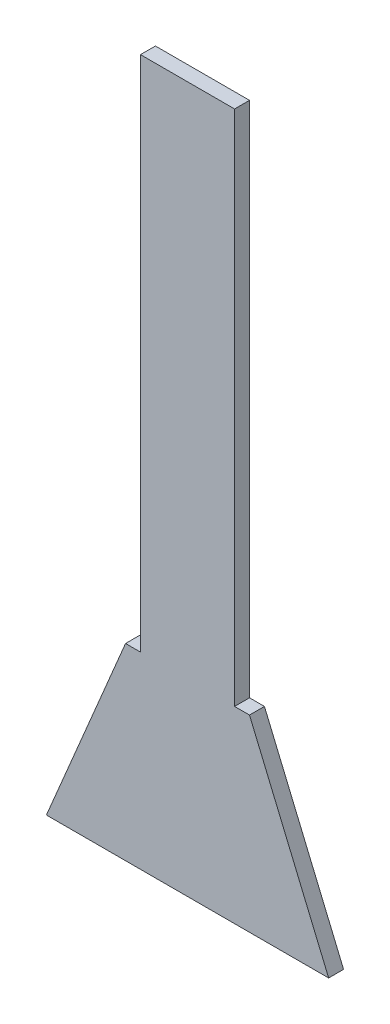
SolidWorks part; units mm, degrees
material "ABS"
ref_plane "Plan de face" through (0, 0, 0) normal (0, 0, 1) x (1, 0, 0)
ref_plane "Plan de dessus" through (0, 0, 0) normal (0, 1, 0) x (1, 0, 0)
ref_plane "Plan de droite" through (0, 0, 0) normal (1, 0, 0) x (0, 0, -1)
sketch "Esquisse1" plane through (0, 0, 0) normal (0, 0, 1) x (1, 0, 0)
  line L1 (-20, 300) -> (20, 300)
  line L2 (-20, 300) -> (-20, 80)
  line L4 (20, 300) -> (20, 80)
  line L8 (-60, 0) -> (60, 0)
  line L9 (26.35, 80) -> (-26.35, 80) construction
  line L10 (26.35, 80) -> (60, 0)
  line L11 (-26.35, 80) -> (-60, 0)
  line L12 (26.35, 80) -> (20, 80)
  line L13 (-20, 80) -> (-26.35, 80)
  point P1 (0, 0)
  point P2 (0, 300)
  point P8 (0, 80)
  dimension "D1" = 80
  dimension "D2" = 120
  dimension "D3" = 40
  dimension "D4" = 300
  dimension "D5" = 6.35
extrude "Boss.-Extru.1" add sketch "Esquisse1" along normal blind 6.35
